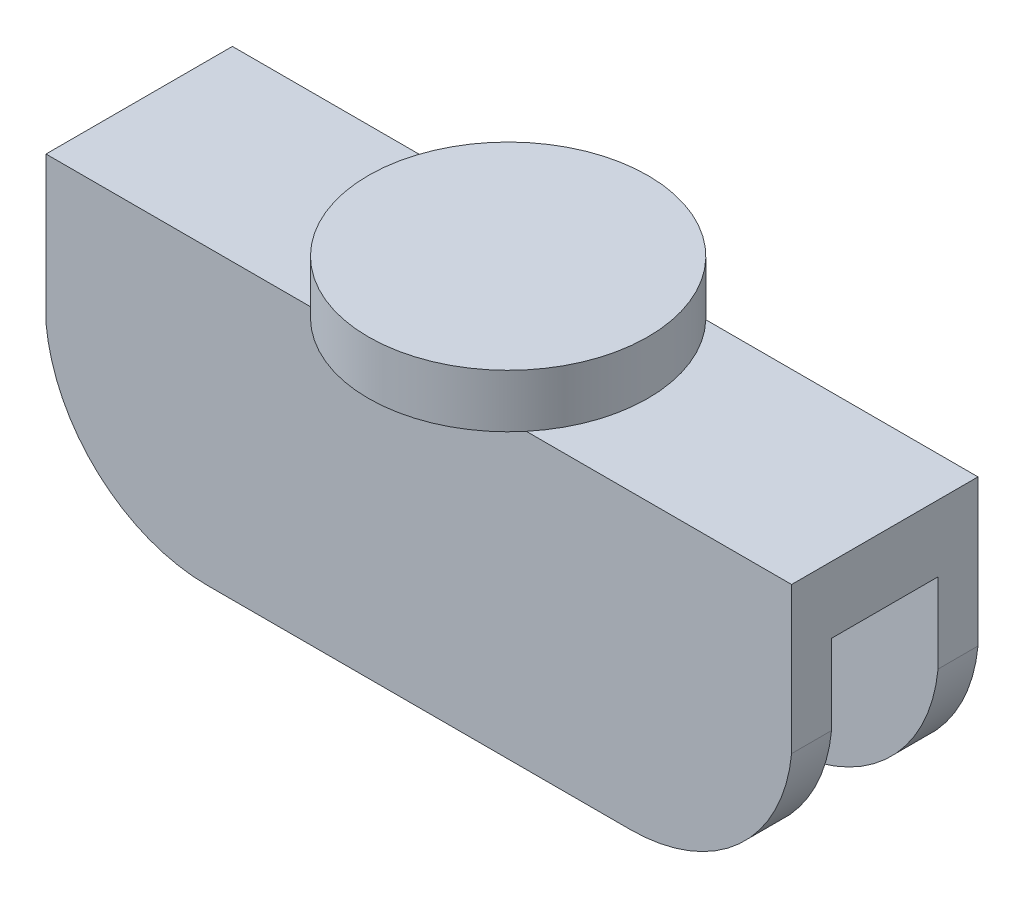
SolidWorks part; units mm, degrees
ref_plane "Front Plane" through (0, 0, 0) normal (0, 0, 1) x (1, 0, 0)
ref_plane "Top Plane" through (0, 0, 0) normal (0, 1, 0) x (1, 0, 0)
ref_plane "Right Plane" through (0, 0, 0) normal (1, 0, 0) x (0, 0, -1)
sketch "Sketch1" plane through (0, 0, 0) normal (0, 0, 1) x (1, 0, 0)
  line L1 (-70, 27.5) -> (70, 27.5)
  line L2 (-70, 27.5) -> (-70, -27.5)
  line L3 (-70, -27.5) -> (70, -27.5)
  line L4 (70, 27.5) -> (70, -27.5)
  line L5 (-70, 27.5) -> (70, -27.5) construction
  line L6 (-70, -27.5) -> (70, 27.5) construction
  point P0 (0, 0)
  dimension "D1" = 55
  dimension "D2" = 140
extrude "Boss-Extrude1" add sketch "Sketch1" along normal blind 35
sketch "Sketch2" plane through (0, 0, 35) normal (0, 0, 1) x (1, 0, 0)
  line L0 (0, -27.5) -> (0, 27.5) construction
  line L1 (-70, -27.5) -> (70, -27.5) construction
  line L2 (70, 27.5) -> (-70, 27.5) construction
  line L3 (39.6838, -27.5) -> (-39.6838, -27.5)
  line L4 (-70, 27.5) -> (-70, -27.5) construction
  line L5 (-70, 27.5) -> (70, 27.5)
  line L6 (-70, 0) -> (-70, -27.5)
  line L7 (-70, -27.5) -> (-39.6838, -27.5)
  line L8 (70, -27.5) -> (70, 0)
  arc A0 (-39.6838, -27.5) -> (-70, 0) centre (-39.6838, 2.9604) cw
  arc A1 (39.6838, -27.5) -> (70, 0) centre (39.6838, 2.9604) ccw
  line M4 (70, -27.5) -> (70, 27.5)
  line M6 (-70, 27.5) -> (-70, -27.5)
  line M7 (-70, -27.5) -> (70, -27.5)
extrude "Cut-Extrude1" cut sketch "Sketch2" against normal blind 120 contours A1 M7 M4 | A0 M7 M6
sketch "Sketch4" plane through (0, 27.5, 0) normal (0, 1, 0) x (1, 0, 0)
  circle A0 centre (0, -18.225) radius 26.25
  dimension "D1" = 52.5
extrude "Boss-Extrude2" add sketch "Sketch4" along normal blind 10
ref_plane "Plane1" through (0, 15, 0) normal (0, 1, 0) x (1, 0, 0)
sketch "Sketch5" plane through (0, 15, 0) normal (0, 1, 0) x (1, 0, 0)
  line L0 (70, 0) -> (70, -35) construction
  line L1 (-70, -7.5) -> (70, -7.5)
  line L2 (-70, -7.5) -> (-70, -27.5)
  line L3 (-70, -27.5) -> (70, -27.5)
  line L4 (70, -7.5) -> (70, -27.5)
  line L6 (-39.6838, 0) -> (39.6838, 0) construction
  line L7 (0, 0) -> (0, -35) construction
  line L8 (20.1906, -35) -> (-20.1906, -35) construction
  point P8 (-70, -17.5)
  dimension "D1" = 20
  dimension "D2" = 17.5
  dimension "D3" = 140
extrude "Cut-Extrude2" cut sketch "Sketch5" against normal through all
